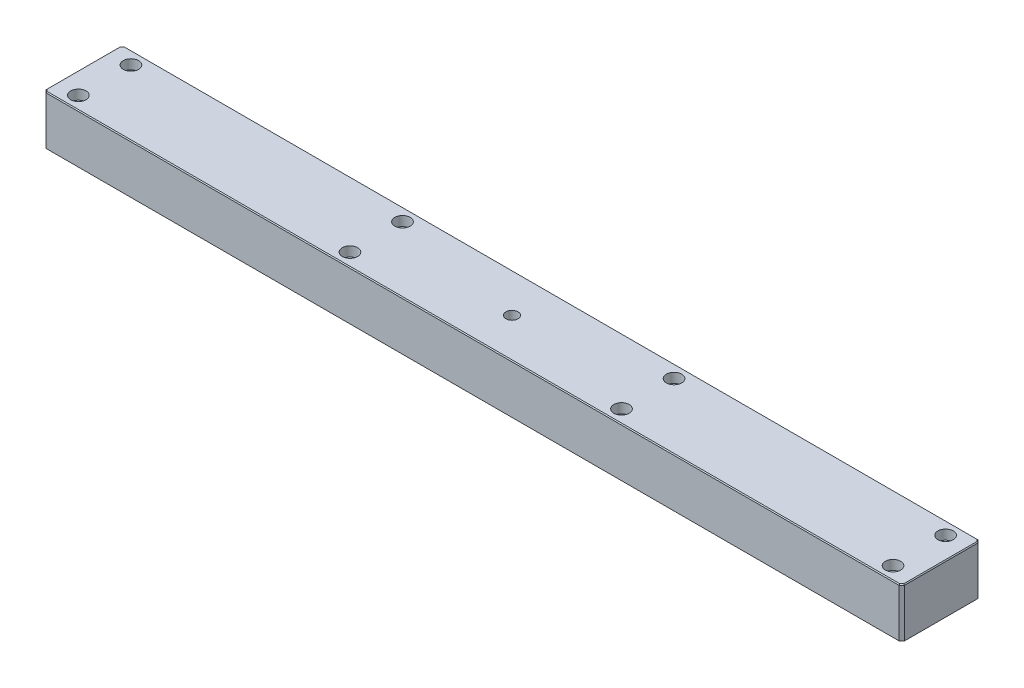
SolidWorks part; units mm, degrees
ref_plane "正面" through (0, 0, 0) normal (0, 0, 1) x (1, 0, 0)
ref_plane "平面" through (0, 0, 0) normal (0, 1, 0) x (1, 0, 0)
ref_plane "右側面" through (0, 0, 0) normal (1, 0, 0) x (0, 0, -1)
sketch "ｽｹｯﾁ1" plane through (0, 0, 0) normal (0, 1, 0) x (1, 0, 0)
  line L0 (-490, -45) -> (490, -45)
  line L1 (490, -45) -> (490, 45)
  line L2 (490, 45) -> (-490, 45)
  line L3 (-490, 45) -> (-490, -45)
extrude "ﾎﾞｽ - 押し出し1" add sketch "ｽｹｯﾁ1" along normal blind 56
chamfer "面取り1" distance 3 angle 45 4 edges at (-490, 28, -45) (490, 28, -45) (490, 28, 45) (-490, 28, 45)
chamfer "面取り2" distance 1 angle 45 8 edges at (488.5, 56, -43.5) (490, 56, 0) (488.5, 56, 43.5) (0, 56, 45) (-488.5, 56, 43.5) (-490, 56, 0) (-488.5, 56, -43.5) (0, 56, -45)
sketch "ｽｹｯﾁ2" plane through (0, 0, 0) normal (0, 1, 0) x (1, 0, 0)
  circle A0 centre (-155, -30) radius 5.5
  circle A1 centre (-155, 30) radius 5.5
  circle A2 centre (-465, -30) radius 5.5
  circle A3 centre (-465, 30) radius 5.5
  circle A4 centre (155, -30) radius 5.5
  circle A5 centre (155, 30) radius 5.5
  circle A6 centre (465, -30) radius 5.5
  circle A7 centre (465, 30) radius 5.5
extrude "ｶｯﾄ - 押し出し1" cut sketch "ｽｹｯﾁ2" against normal through all and the other way through all
ref_plane "平面1" through (0, 56, 0) normal (0, 1, 0) x (1, 0, 0)
sketch "ｽｹｯﾁ4" plane through (0, 56, 0) normal (0, 1, 0) x (1, 0, 0)
  circle A0 centre (-155, -30) radius 8.75
  circle A1 centre (-155, 30) radius 8.75
  circle A2 centre (-465, -30) radius 8.75
  circle A3 centre (-465, 30) radius 8.75
  circle A4 centre (155, -30) radius 8.75
  circle A5 centre (155, 30) radius 8.75
  circle A6 centre (465, -30) radius 8.75
  circle A7 centre (465, 30) radius 8.75
extrude "ｶｯﾄ - 押し出し2" cut sketch "ｽｹｯﾁ4" against normal blind 11
sketch "ｽｹｯﾁ5" plane through (0, 56, 0) normal (0, 1, 0) x (1, 0, 0)
  circle A0 centre (0, 0) radius 6.9175
extrude "ｶｯﾄ - 押し出し3" cut sketch "ｽｹｯﾁ5" against normal blind 25
